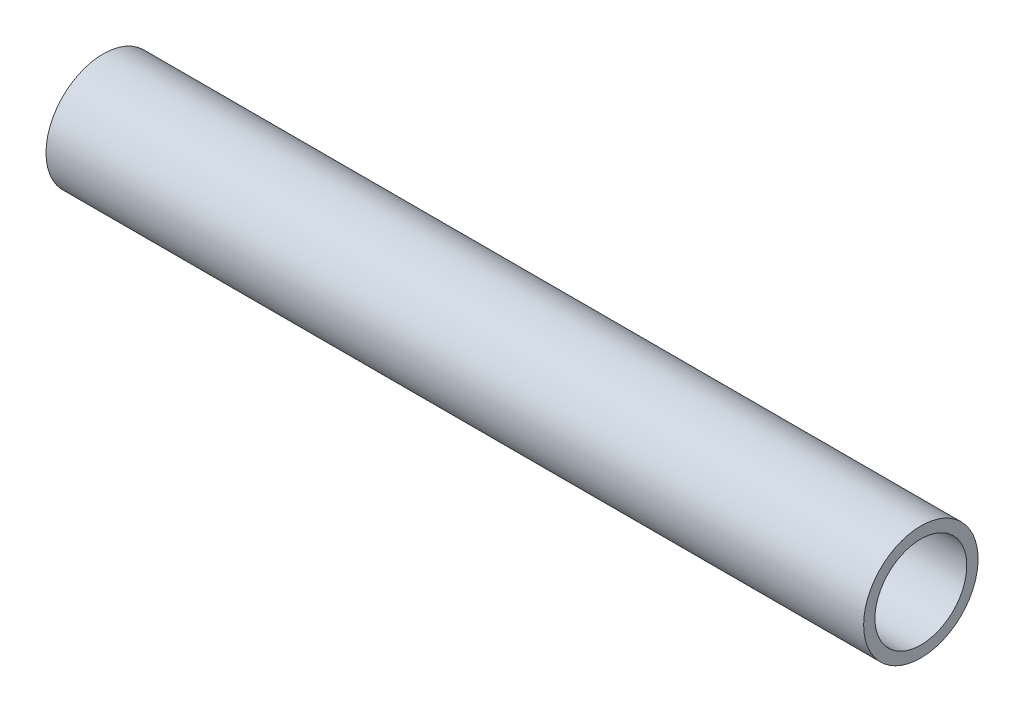
SolidWorks part; units mm, degrees
ref_plane "Front" through (0, 0, 0) normal (0, 0, 1) x (1, 0, 0)
ref_plane "Top" through (0, 0, 0) normal (0, 1, 0) x (1, 0, 0)
ref_plane "Right" through (0, 0, 0) normal (1, 0, 0) x (0, 0, -1)
sketch "Sketch1" plane through (0, 0, 0) normal (1, 0, 0) x (0, 0, -1)
  circle A0 centre (0, 0) radius 10.668
  circle A1 centre (0, 0) radius 8.5598
  point P4 (10.668, 0)
  point P5 (8.5598, 0)
  dimension "Pipe OD" = 21.336
  dimension "ID" = 17.1196
  dimension "Wall" = 2.1082
extrude "Extrude1" add sketch "Sketch1" along normal mid plane 152.4
